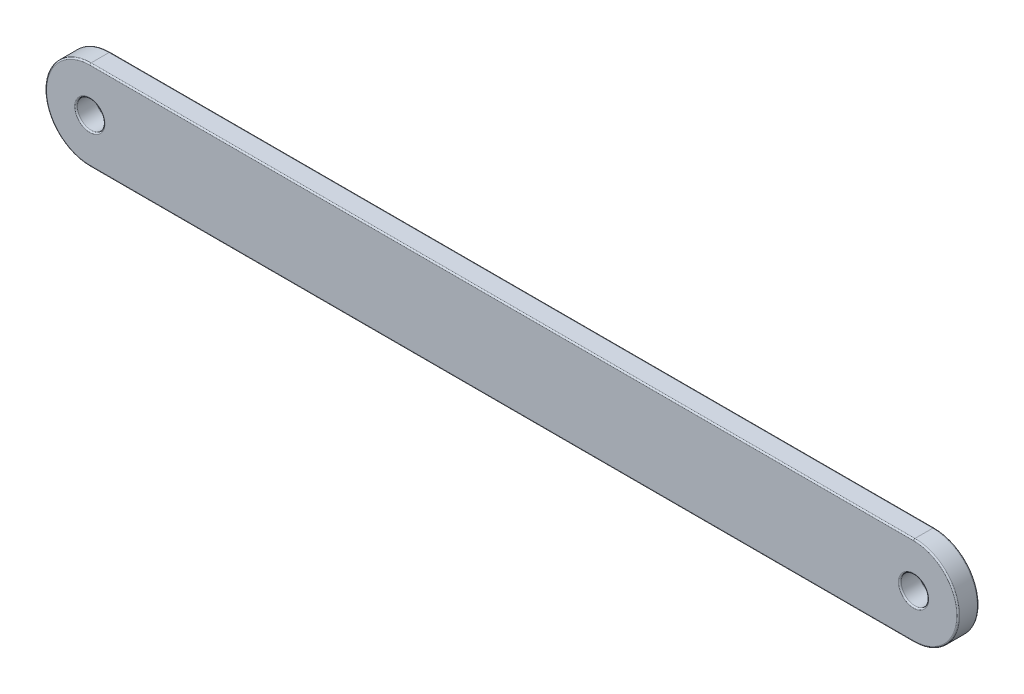
SolidWorks part; units mm, degrees
ref_plane "Alzado" through (0, 0, 0) normal (0, 0, 1) x (1, 0, 0)
ref_plane "Planta" through (0, 0, 0) normal (0, 1, 0) x (1, 0, 0)
ref_plane "Vista lateral" through (0, 0, 0) normal (1, 0, 0) x (0, 0, -1)
sketch "Croquis1" plane through (0, 0, 0) normal (0, 0, 1) x (1, 0, 0)
  line L0 (-30, 0) -> (30, 0) construction
  line L1 (-30, 3.25) -> (30, 3.25)
  line L2 (-30, -3.25) -> (30, -3.25)
  arc A0 (-30, 3.25) -> (-30, -3.25) centre (-30, 0) ccw
  arc A1 (30, -3.25) -> (30, 3.25) centre (30, 0) ccw
  circle A2 centre (-30, 0) radius 1
  circle A3 centre (30, 0) radius 1
  point P2 (0, 0)
  dimension "D2" = 3.25
  dimension "D3" = 2
  dimension "D1" = 60
extrude "Saliente-Extruir1" add sketch "Croquis1" along normal blind 1.5
fillet "Redondeo1" radius 0.1 12 edges at (31, 0, 0) (31, 0, 1.5) (-29, 0, 0) (-29, 0, 1.5) (-33.25, 0, 0) (0, -3.25, 0) (33.25, 0, 0) (0, 3.25, 0) (-33.25, 0, 1.5) (0, -3.25, 1.5) (33.25, 0, 1.5) (0, 3.25, 1.5)
